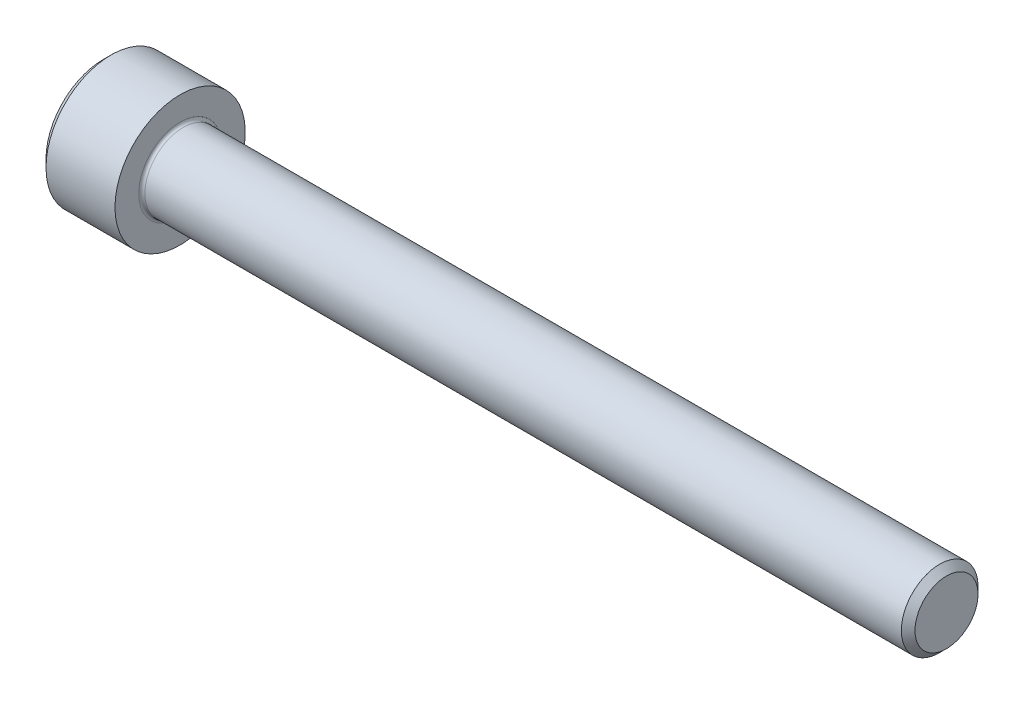
SolidWorks part; units mm, degrees
revolve "Base-Revolve" add sketch "BodySke"
sketch "BodySke" plane through (0, 0, 0) normal (0, 0, 1) x (1, 0, 0)
  line L0 (0, 0) -> (0, 3.75)
  line L1 (0.5, 4.25) -> (5, 4.25)
  line L2 (5, 4.25) -> (5, 2.5)
  line L3 (5, 2.5) -> (54.555, 2.5)
  line L4 (55, 2.055) -> (55, 0)
  line L5 (55, 0) -> (0, 0)
  line L6 (-31.75, 0) -> (127, 0) construction
  line L7 (0, 3.75) -> (0.5, 4.25)
  line L8 (55, 2.055) -> (54.555, 2.5)
  line L9 (0, -3.75) -> (0.5, -4.25) construction
  line L10 (55, -2.055) -> (54.555, -2.5) construction
  line L11 (5.8, 9.525) -> (5.8, 3.175) construction
  line L12 (33, 9.525) -> (33, 3.175) construction
  line L13 (5, 9.525) -> (5, 3.175) construction
  dimension "Diameter" = 5
  dimension "Head_ht" = 5
  dimension "Length" = 50
  dimension "Body_ch_ang" = 45
  dimension "Head_dia" = 8.5
  dimension "Head_ch_ang" = 45
  dimension "Minor_dia" = 4.11
  dimension "Advance" = 0.8
  dimension "Thread_nom" = 22
  dimension "Thread_length" = 50
  dimension "Head_ch_ht" = 0.5
cosmetic thread "ThreadCosmetic" [suppressed]
fillet "Fillet1" radius 0.2 1 edges at (5, 0, 2.5)
ref_plane "Plane1" through (0, 0, 0) normal (0, 0, 1) x (1, 0, 0)
ref_plane "Plane2" through (0, 0, 0) normal (0, 1, 0) x (1, 0, 0)
ref_plane "Plane3" through (0, 0, 0) normal (1, 0, 0) x (0, 0, -1)
sketch "Sketch2" plane through (0, 0, 0) normal (0, 0, 1) x (1, 0, 0)
  line L0 (0, 2.042) -> (2.5, 2.042)
  line L1 (2.5, 2.042) -> (3.6789, 0)
  line L2 (-31.75, 0) -> (127, 0) construction
  line L3 (3.6789, 0) -> (0, 0)
  line L4 (0, 0) -> (0, 2.042)
  line L5 (0, 3.75) -> (0, -3.75) construction
  line L6 (0, 0) -> (47.625, 0) construction
  line L7 (5, -4.25) -> (5, 4.25) construction
  dimension "D1" = 2.042
  dimension "D2" = 60
revolve "Hex-PreBroach" cut sketch "Sketch2" angle 360 about L6
sketch "Sketch3" plane through (0, 0, 0) normal (-1, 0, 0) x (0, 0.5, 0.866)
  line L0 (1.1789, 2.042) -> (-1.1789, 2.042)
  line L1 (-1.1789, 2.042) -> (-2.3579, 0)
  line L2 (1.1789, 2.042) -> (2.3579, 0)
  line L3 (1.1789, -2.042) -> (2.3579, 0)
  line L4 (1.1789, -2.042) -> (-1.1789, -2.042)
  line L5 (-1.1789, -2.042) -> (-2.3579, 0)
  dimension "D1" = 2.042
  dimension "D2" = 2.042
  dimension "Hex_size" = 4.084
extrude "Hex" cut sketch "Sketch3" against normal blind 2.5
sketch "Sketch4" plane through (0, 0, 0) normal (-1, 0, 0) x (0, 0, 1)
  line L0 (0, 0) -> (2.3876, 0)
  line L1 (0, 0) -> (6.1484, 3.5498) construction
  line L2 (0, 0) -> (1.1938, 2.0677)
  line L3 (1.9883, 0.576) -> (2.2704, 0.7389)
  line L4 (1.493, 1.4339) -> (1.7751, 1.5968)
  arc A0 (1.9883, 0.576) -> (1.493, 1.4339) centre (0, 0) ccw
  arc A1 (2.3876, 0) -> (2.2704, 0.7389) centre (0, 0) ccw
  arc A2 (1.1938, 2.0677) -> (1.7751, 1.5968) centre (0, 0) cw
  dimension "D1" = 30
  dimension "D2" = 60
  dimension "Spline_p_dim" = 0.9906
  dimension "D3" = 0.4953
extrude "Spline" [suppressed] cut sketch "Sketch4" against normal blind 2.5
pattern_circular "CirPattern1" [suppressed] count 6 every 60
sketch "Sketch5" plane through (0, 0, 0) normal (0, 0, 1) x (1, 0, 0)
  line L0 (-31.75, 0) -> (127, 0) construction
  line L2 (0, 3.75) -> (0, -3.75) construction
  circle A0 centre (2, 0) radius 0.675
  dimension "Drilled_hole_dia" = 1.35
  dimension "Drilled_hole_loc" = 2
extrude "Hole" [suppressed] cut sketch "Sketch5" against normal through all and the other way through all
pattern_circular "Drilled-4" [suppressed] count 2 every 60
pattern_circular "Drilled-6" [suppressed] count 3 every 60
sketch "ThdSchSke" plane through (0, 0, 0) normal (0, 0, 1) x (1, 0, 0)
  line L0 (33, -2.055) -> (32.6884, -2.5)
  line L1 (33, -2.055) -> (33.3116, -2.5)
  line L2 (33.3116, -2.5) -> (33.3116, -3.125)
  line L3 (-3.175, 0) -> (5.1513, 0) construction
  line L5 (33.3116, -3.125) -> (32.6884, -3.125)
  line L6 (32.6884, -3.125) -> (32.6884, -2.5)
  line L7 (0, 3.75) -> (0, -3.75) construction
  dimension "Thread_minor" = 4.11
  dimension "Diameter" = 5
  dimension "Start" = 33
revolve "ThreadSchematic" [suppressed] cut sketch "ThdSchSke" angle 360 about L3
pattern_linear "ThdSchPat" [suppressed]
equation "\"D2@Sketch3\" = \"Hex_size@Sketch3\" / 2"
equation "\"D1@Sketch3\" = \"Hex_size@Sketch3\" / 2"
equation "\"D1@Sketch2\" = \"Hex_size@Sketch3\" / 2"
equation "\"D3@Sketch4\" = \"Spline_p_dim@Sketch4\" / 2"
equation "\"Thread_minor@ThreadCosmetic\"  =  \"Minor_dia@BodySke\""
equation "\"D2@CirPattern1\" = 360 / \"Num_teeth@CirPattern1\""
equation "\"Wall_thickness@Sketch2\" = \"Head_ht@BodySke\" - \"Key_eng@Hex\""
equation "\"Thread_length@ThreadCosmetic\" = ((sgn( (\"Length@BodySke\" - \"Advance@BodySke\" ) - \"Thread_nom@BodySke\" )-1)*( (\"Length@BodySke\" - \"Advance@BodySke\" ) - \"Thread_nom@BodySke\" ))/-2+ \"Thread_nom@BodySke\""
equation "\"Thread_minor@ThdSchSke\" = \"Minor_dia@BodySke\""
equation "\"Diameter@ThdSchSke\" = \"Diameter@BodySke\""
equation "\"Overcut@ThdSchSke\" = \"Diameter@BodySke\" * 1.25"
equation "\"Start@ThdSchSke\" = \"Head_ht@BodySke\" + \"Length@BodySke\" - \"Thread_length@ThreadCosmetic\"  '---Non-countersunk---"
equation "\"Num_threads@ThdSchPat\" = int( \"Thread_length@ThreadCosmetic\" / \"Advance@BodySke\" + 0.999 )  + 1"
equation "\"Advance@ThdSchPat\" = \"Thread_length@ThreadCosmetic\" /  (\"Num_threads@ThdSchPat\" - 1) 'relax it"
equation "\"Num_threads@ThdSchPat\" = \"Num_threads@ThdSchPat\" - sgn( \"Num_threads@ThdSchPat\" - 1) '---chamfered tips only---"
